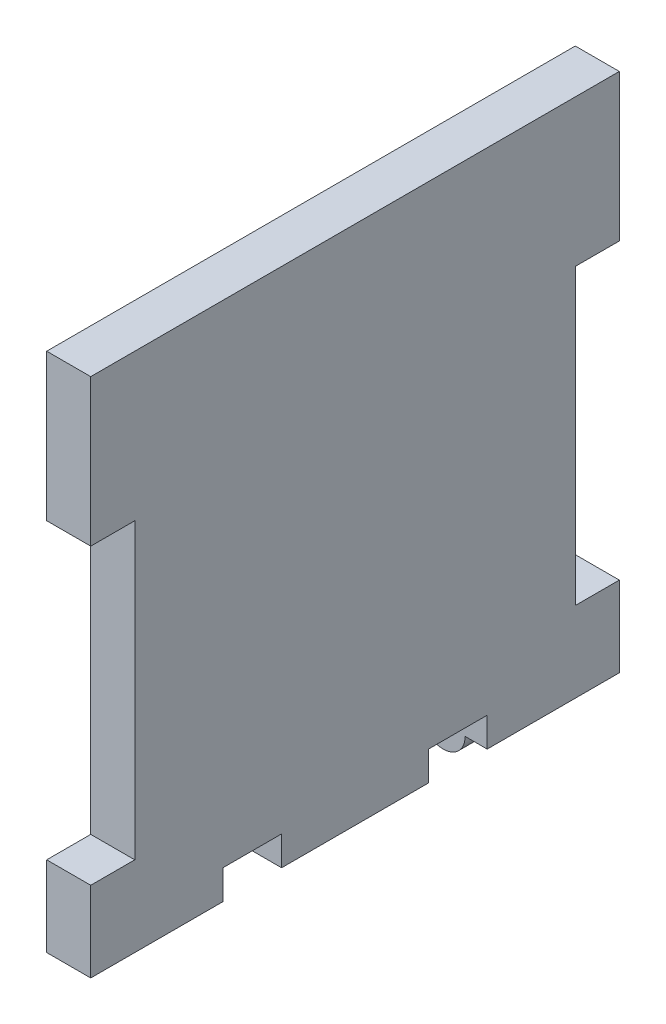
SolidWorks part; units mm, degrees
material "Acrilico TEC"
ref_plane "Front Plane" through (0, 0, 0) normal (0, 0, 1) x (1, 0, 0)
ref_plane "Top Plane" through (0, 0, 0) normal (0, 1, 0) x (1, 0, 0)
ref_plane "Right Plane" through (0, 0, 0) normal (1, 0, 0) x (0, 0, -1)
sketch "Sketch1" plane through (0, 0, 0) normal (1, 0, 0) x (0, 0, -1)
  line L0 (-15, 0) -> (15, 0)
  line L1 (-18, 25.47) -> (-18, 35.47)
  line L2 (15, 5.47) -> (18, 5.47)
  line L3 (-15, 5.47) -> (-15, 25.47)
  line L4 (18, 25.47) -> (15, 25.47)
  line L5 (-18, 0) -> (-18, 5.47)
  line L6 (15, 35.47) -> (-15, 35.47)
  line L7 (0, 35.47) -> (0, 0) construction
  line L8 (-18, 25.47) -> (-15, 25.47)
  line L9 (-15, 5.47) -> (-18, 5.47)
  line L10 (-18, 35.47) -> (-15, 35.47)
  line L11 (-18, 0) -> (-15, 0)
  line L13 (15, 0) -> (18, 0)
  line L14 (18, 0) -> (18, 5.47)
  line L15 (15, 5.47) -> (15, 25.47)
  line L16 (18, 25.47) -> (18, 35.47)
  line L17 (18, 35.47) -> (15, 35.47)
  dimension "D1" = 15
  dimension "D2" = 5.47
  dimension "D3" = 3
  dimension "D4" = 10
  dimension "D5" = 20
extrude "Boss-Extrude1" add sketch "Sketch1" along normal blind 3
ref_plane "Plane1" through (0, 0, 12) normal (0, 0, 1) x (1, 0, 0)
sketch "Sketch4" plane through (0, 0, 12) normal (0, 0, 1) x (1, 0, 0)
  circle A0 centre (0, 0) radius 1.5
  dimension "D1" = 3
extrude "Boss-Extrude2" add sketch "Sketch4" against normal blind 3
pattern_linear "LPattern1" count 1 spacing 10 along (0, 0, -1) count 2 spacing 21 along (0, 0, -1) of "Boss-Extrude2"
sketch "Sketch5" plane through (0, 0, 0) normal (-1, 0, 0) x (0, 0, 1)
  line L0 (9, 0) -> (-9, 0) construction
  line L1 (-9, 0) -> (-5, 0)
  line L2 (-9, 0) -> (-9, 2)
  line L3 (-9, 2) -> (-5, 2)
  line L4 (-5, 0) -> (-5, 2)
  line L5 (0, 0) -> (0, 14.9587) construction
  line L6 (5, 0) -> (5, 2)
  line L7 (9, 2) -> (5, 2)
  line L8 (9, 0) -> (9, 2)
  line L9 (9, 0) -> (5, 0)
  dimension "D1" = 4
  dimension "D2" = 2
extrude "Cut-Extrude1" cut sketch "Sketch5" against normal blind 10
